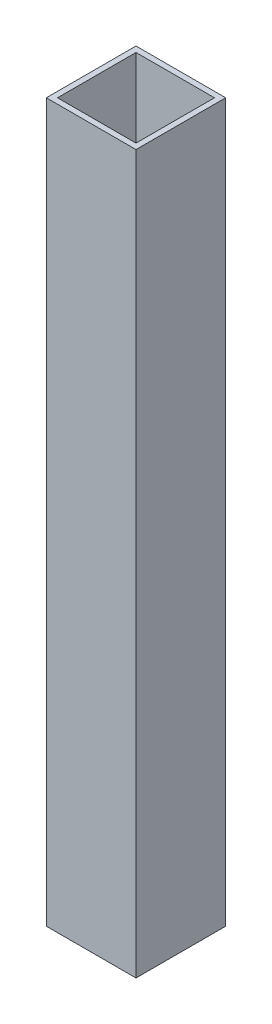
SolidWorks part; units mm, degrees
ref_plane "Front Plane" through (0, 0, 0) normal (0, 0, 1) x (1, 0, 0)
ref_plane "Top Plane" through (0, 0, 0) normal (0, 1, 0) x (1, 0, 0)
ref_plane "Right Plane" through (0, 0, 0) normal (1, 0, 0) x (0, 0, -1)
sketch "Sketch1" plane through (0, 0, 0) normal (0, 1, 0) x (1, 0, 0)
  line L1 (12.7, 12.7) -> (-12.7, 12.7)
  line L2 (12.7, 12.7) -> (12.7, -12.7)
  line L3 (12.7, -12.7) -> (-12.7, -12.7)
  line L4 (-12.7, 12.7) -> (-12.7, -12.7)
  line L5 (12.7, 12.7) -> (-12.7, -12.7) construction
  line L6 (12.7, -12.7) -> (-12.7, 12.7) construction
  line L7 (11.1125, 11.1125) -> (-11.1125, 11.1125)
  line L8 (11.1125, 11.1125) -> (11.1125, -11.1125)
  line L9 (11.1125, -11.1125) -> (-11.1125, -11.1125)
  line L10 (-11.1125, 11.1125) -> (-11.1125, -11.1125)
  line L11 (11.1125, 11.1125) -> (-11.1125, -11.1125) construction
  line L12 (11.1125, -11.1125) -> (-11.1125, 11.1125) construction
  point P0 (0, 0)
  point P6 (0, 0)
  dimension "D1" = 25.4
  dimension "D2" = 25.4
  dimension "D3" = 1.5875
  dimension "D4" = 1.5875
extrude "Boss-Extrude1" add sketch "Sketch1" along normal blind 203.2
